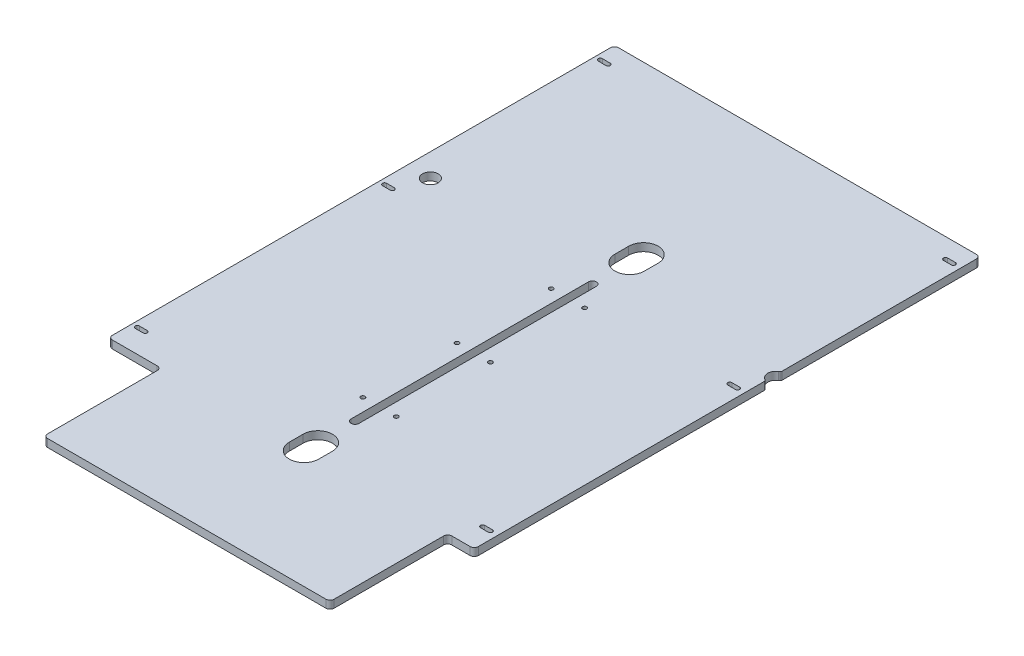
SolidWorks part; units mm, degrees
material "PE High Density"
ref_plane "Front" through (0, 0, 0) normal (0, 0, 1) x (1, 0, 0)
ref_plane "Top" through (0, 0, 0) normal (0, 1, 0) x (1, 0, 0)
ref_plane "Right" through (0, 0, 0) normal (1, 0, 0) x (0, 0, -1)
sketch "Sketch1" plane through (0, 0, 0) normal (0, 1, 0) x (1, 0, 0)
  line L0 (0, 0) -> (96.0438, 0)
  line L1 (96.0438, 0) -> (96.0438, -190.5)
  line L2 (96.0438, -190.5) -> (559.5938, -190.5)
  line L3 (559.5938, -190.5) -> (559.5938, 0)
  line L4 (559.5938, 0) -> (606.425, 0)
  line L5 (606.425, 0) -> (606.425, 819.15)
  line L6 (606.425, 819.15) -> (0, 819.15)
  line L7 (0, 819.15) -> (0, 0)
  line L8 (25.4, 0) -> (25.4, 819.15) construction
  line L9 (19.05, 38.1) -> (31.75, 38.1) construction
  line L10 (19.05, 41.4782) -> (31.75, 41.4782)
  line L11 (19.05, 34.7218) -> (31.75, 34.7218)
  line L12 (19.05, 438.15) -> (31.75, 438.15) construction
  line L13 (19.05, 441.5282) -> (31.75, 441.5282)
  line L14 (19.05, 434.7718) -> (31.75, 434.7718)
  line L15 (31.75, 787.4) -> (19.05, 787.4) construction
  line L16 (31.75, 784.0218) -> (19.05, 784.0218)
  line L17 (31.75, 790.7782) -> (19.05, 790.7782)
  line L18 (303.2125, 819.15) -> (303.2125, -190.5) construction
  line L19 (584.2, 787.4) -> (584.2, 438.15) construction
  line L20 (577.85, 787.4) -> (590.55, 787.4) construction
  line L21 (577.85, 784.0218) -> (590.55, 784.0218)
  line L22 (577.85, 790.7782) -> (590.55, 790.7782)
  line L23 (590.55, 438.15) -> (577.85, 438.15) construction
  line L24 (590.55, 441.5282) -> (577.85, 441.5282)
  line L25 (590.55, 434.7718) -> (577.85, 434.7718)
  line L26 (590.55, 38.1) -> (577.85, 38.1) construction
  line L27 (590.55, 41.4782) -> (577.85, 41.4782)
  line L28 (590.55, 34.7218) -> (577.85, 34.7218)
  line L29 (327.8187, -190.5) -> (327.8187, 819.15) construction
  line L30 (584.2, 438.15) -> (584.2, 38.1) construction
  arc A1 (19.05, 41.4782) -> (19.05, 34.7218) centre (19.05, 38.1) ccw
  arc A2 (31.75, 34.7218) -> (31.75, 41.4782) centre (31.75, 38.1) ccw
  arc A3 (19.05, 441.5282) -> (19.05, 434.7718) centre (19.05, 438.15) ccw
  arc A4 (31.75, 434.7718) -> (31.75, 441.5282) centre (31.75, 438.15) ccw
  arc A5 (31.75, 784.0218) -> (31.75, 790.7782) centre (31.75, 787.4) ccw
  arc A6 (19.05, 790.7782) -> (19.05, 784.0218) centre (19.05, 787.4) ccw
  arc A7 (577.85, 784.0218) -> (577.85, 790.7782) centre (577.85, 787.4) cw
  arc A8 (590.55, 790.7782) -> (590.55, 784.0218) centre (590.55, 787.4) cw
  arc A9 (590.55, 441.5282) -> (590.55, 434.7718) centre (590.55, 438.15) cw
  arc A10 (577.85, 434.7718) -> (577.85, 441.5282) centre (577.85, 438.15) cw
  arc A11 (590.55, 41.4782) -> (590.55, 34.7218) centre (590.55, 38.1) cw
  arc A12 (577.85, 34.7218) -> (577.85, 41.4782) centre (577.85, 38.1) cw
  point P13 (25.4, 38.1)
  point P20 (25.4, 438.15)
  point P27 (25.4, 787.4)
  point P38 (584.2, 787.4)
  point P45 (584.2, 438.15)
  point P52 (584.2, 38.1)
  dimension "D1" = 96.0438
  dimension "D2" = 46.8312
  dimension "D3" = 819.15
  dimension "D4" = 25.4
  dimension "D5" = 6.7564
  dimension "D6" = 38.1
  dimension "D7" = 12.7
  dimension "D8" = 400.05
  dimension "D9" = 349.25
  dimension "D10" = 190.5
  dimension "D11" = 463.55
  dimension "D12" = 22.225
extrude "Boss-Extrude1" add sketch "Sketch1" along normal blind 12.7
fillet "Fillet1" radius 6.604 2 edges at (96.0438, 6.35, 0) (559.5938, 6.35, 0)
fillet "Fillet2" radius 6.604 6 edges at (0, 6.35, -819.15) (606.425, 6.35, -819.15) (606.425, 6.35, 0) (559.5938, 6.35, 190.5) (0, 6.35, 0) (96.0438, 6.35, 190.5)
sketch "Sketch2" plane through (0, 12.7, 0) normal (0, 1, 0) x (1, 0, 0)
  line L1 (606.425, 6.604) -> (606.425, 812.546) construction
  line L3 (577.85, 438.15) -> (590.55, 438.15) construction
  line L4 (606.425, 505.867) -> (606.425, 461.873)
  line L5 (606.425, 483.87) -> (47.625, 483.87) construction
  line L6 (0, 812.546) -> (0, 6.604) construction
  arc A3 (600.075, 494.8685) -> (600.075, 472.8715) centre (606.425, 483.87) ccw
  arc A4 (600.075, 494.8685) -> (606.425, 505.867) centre (593.725, 505.867) ccw
  arc A5 (606.425, 461.873) -> (600.075, 472.8715) centre (593.725, 461.873) ccw
  circle A6 centre (47.625, 483.87) radius 12.7
  dimension "D1" = 25.4
  dimension "D2" = 45.72
  dimension "D3" = 47.625
extrude "Cut-Extrude1" cut sketch "Sketch2" against normal through all
sketch "Sketch4" plane through (0, 0, 0) normal (0, -1, 0) x (1, 0, 0)
  line L0 (0, -812.546) -> (0, -6.604) construction
  line L3 (327.025, -527.05) -> (327.025, -549.275) construction
  line L4 (350.8375, -527.05) -> (350.8375, -549.275)
  line L5 (303.2125, -527.05) -> (303.2125, -549.275)
  line L7 (599.821, -819.15) -> (6.604, -819.15) construction
  line L8 (327.025, 0) -> (327.025, -22.225) construction
  line L9 (350.8375, 0) -> (350.8375, -22.225)
  line L10 (303.2125, 0) -> (303.2125, -22.225)
  circle A0 centre (327.025, -538.1625) radius 28.575 construction
  arc A2 (350.8375, -527.05) -> (303.2125, -527.05) centre (327.025, -527.05) ccw
  arc A3 (303.2125, -549.275) -> (350.8375, -549.275) centre (327.025, -549.275) ccw
  arc A4 (350.8375, 0) -> (303.2125, 0) centre (327.025, 0) ccw
  arc A5 (303.2125, -22.225) -> (350.8375, -22.225) centre (327.025, -22.225) ccw
  point P8 (327.025, -11.1125)
  point P12 (327.025, -538.1625)
  dimension "D2" = 57.15
  dimension "D1" = 327.025
  dimension "D3" = 527.05
  dimension "D4" = 47.625
  dimension "D5" = 22.225
  dimension "D6" = 280.9875
extrude "Cut-Extrude3" cut sketch "Sketch4" against normal through all
sketch "Sketch5" plane through (0, 0, 0) normal (0, -1, 0) x (1, 0, 0)
  line L0 (327.025, -22.225) -> (327.025, -527.05) construction
  line L1 (327.025, -466.725) -> (327.025, -82.55) construction
  line L2 (320.675, -466.725) -> (320.675, -82.55)
  line L3 (333.375, -466.725) -> (333.375, -82.55)
  arc A0 (320.675, -466.725) -> (333.375, -466.725) centre (327.025, -466.725) ccw
  arc A1 (333.375, -82.55) -> (320.675, -82.55) centre (327.025, -82.55) ccw
  point P6 (327.025, -274.6375)
  dimension "D1" = 384.175
  dimension "D2" = 12.7
extrude "Cut-Extrude4" cut sketch "Sketch5" against normal through all
sketch "Sketch6" plane through (0, 0, 0) normal (0, -1, 0) x (1, 0, 0)
  line L0 (327.025, -82.55) -> (327.025, -466.725) construction
  line L1 (327.025, -274.6375) -> (354.0125, -274.6375) construction
  line L2 (354.0125, -122.2375) -> (354.0125, -427.0375) construction
  line L3 (300.0375, -122.2375) -> (300.0375, -427.0375) construction
  circle A0 centre (354.0125, -274.6375) radius 3.3782
  circle A1 centre (354.0125, -427.0375) radius 3.3782
  circle A2 centre (354.0125, -122.2375) radius 3.3782
  circle A3 centre (300.0375, -427.0375) radius 3.3782
  circle A4 centre (300.0375, -274.6375) radius 3.3782
  circle A5 centre (300.0375, -122.2375) radius 3.3782
  dimension "D2" = 6.7564
  dimension "D1" = 26.9875
  dimension "D3" = 152.4
extrude "Cut-Extrude5" cut sketch "Sketch6" against normal through all
sketch "Sketch7" plane through (0, 0, 0) normal (0, -1, 0) x (1, 0, 0)
  line L0 (599.821, -819.15) -> (6.604, -819.15) construction
  line L1 (6.604, 0) -> (89.4398, 0) construction
  line L2 (0, -812.546) -> (0, -6.604) construction
  line L3 (7.366, -819.15) -> (6.604, -819.15)
  line L4 (6.604, 0) -> (7.366, 0)
  line L5 (0, -812.546) -> (0, -6.604)
  line L6 (0.762, -6.604) -> (0.762, -812.546)
  line L7 (566.1978, 0) -> (599.821, 0) construction
  line L8 (606.425, -505.867) -> (606.425, -812.546) construction
  line L9 (606.425, -6.604) -> (606.425, -461.873) construction
  line L10 (566.1978, 0) -> (599.821, 0)
  line L11 (599.821, -819.15) -> (6.604, -819.15)
  line L12 (606.425, -505.867) -> (606.425, -812.546)
  line L13 (606.425, -6.604) -> (606.425, -461.873)
  line L14 (605.663, -504.5472) -> (605.663, -812.546)
  line L15 (605.663, -6.604) -> (605.663, -462.3309)
  arc A0 (0, -812.546) -> (6.604, -819.15) centre (6.604, -812.546) ccw construction
  arc A1 (6.604, 0) -> (0, -6.604) centre (6.604, -6.604) ccw construction
  arc A2 (0, -812.546) -> (6.604, -819.15) centre (6.604, -812.546) ccw
  arc A3 (6.604, 0) -> (0, -6.604) centre (6.604, -6.604) ccw
  arc A4 (7.366, 0) -> (0.762, -6.604) centre (7.366, -6.604) ccw
  arc A5 (0.762, -812.546) -> (7.366, -819.15) centre (7.366, -812.546) ccw
  arc A6 (599.821, -819.15) -> (606.425, -812.546) centre (599.821, -812.546) ccw construction
  arc A7 (606.425, -505.867) -> (600.075, -494.8685) centre (593.725, -505.867) ccw construction
  arc A8 (600.075, -472.8715) -> (600.075, -494.8685) centre (606.425, -483.87) ccw construction
  arc A9 (600.075, -472.8715) -> (606.425, -461.873) centre (593.725, -461.873) ccw construction
  arc A10 (606.425, -6.604) -> (599.821, 0) centre (599.821, -6.604) ccw construction
  arc A11 (599.821, -819.15) -> (606.425, -812.546) centre (599.821, -812.546) ccw
  arc A12 (606.425, -505.867) -> (600.075, -494.8685) centre (593.725, -505.867) ccw
  arc A13 (600.075, -472.8715) -> (600.075, -494.8685) centre (606.425, -483.87) ccw
  arc A14 (600.075, -472.8715) -> (606.425, -461.873) centre (593.725, -461.873) ccw
  arc A15 (606.425, -6.604) -> (599.821, 0) centre (599.821, -6.604) ccw
  arc A16 (605.663, -6.604) -> (599.059, 0) centre (599.059, -6.604) ccw
  arc A17 (599.059, -819.15) -> (605.663, -812.546) centre (599.059, -812.546) ccw
  arc A18 (605.663, -504.5472) -> (600.075, -494.8685) centre (594.487, -504.5472) ccw
  arc A19 (599.694, -473.1004) -> (605.663, -462.3309) centre (592.963, -462.3309) ccw
  dimension "D1" = 0.762
  dimension "D2" = 0.762
extrude "Cut-Extrude6" cut sketch "Sketch7" against normal through all contours A18 L14 A17 L11 A11 L12 A12 | A5 L6 A4 L4 A3 L5 A2 L3 | A19 A13 A14 L13 A15 L10 A16 L15
sketch "Sketch8" plane through (0, 0, 0) normal (0, -1, 0) x (1, 0, 0)
  line L0 (0.762, -6.604) -> (0.762, -812.546) construction
  line L1 (0.762, -6.604) -> (0.762, -812.546)
  line L2 (605.663, -6.604) -> (605.663, -462.3309) construction
  line L3 (605.663, -6.604) -> (605.663, -812.546)
  line L4 (10.287, -6.604) -> (10.287, -812.546)
  line L5 (16.891, 0) -> (7.366, 0)
  line L6 (16.891, -819.15) -> (7.366, -819.15)
  line L7 (602.488, -6.604) -> (602.488, -812.546)
  line L8 (599.059, -819.15) -> (595.884, -819.15)
  line L9 (599.059, 0) -> (595.884, 0)
  arc A0 (0.762, -812.546) -> (7.366, -819.15) centre (7.366, -812.546) ccw construction
  arc A1 (7.366, 0) -> (0.762, -6.604) centre (7.366, -6.604) ccw construction
  arc A2 (0.762, -812.546) -> (7.366, -819.15) centre (7.366, -812.546) ccw
  arc A3 (7.366, 0) -> (0.762, -6.604) centre (7.366, -6.604) ccw
  arc A4 (599.059, -819.15) -> (605.663, -812.546) centre (599.059, -812.546) ccw construction
  arc A5 (605.663, -6.604) -> (599.059, 0) centre (599.059, -6.604) ccw construction
  arc A6 (599.059, -819.15) -> (605.663, -812.546) centre (599.059, -812.546) ccw
  arc A7 (605.663, -6.604) -> (599.059, 0) centre (599.059, -6.604) ccw
  arc A8 (16.891, 0) -> (10.287, -6.604) centre (16.891, -6.604) ccw
  arc A9 (10.287, -812.546) -> (16.891, -819.15) centre (16.891, -812.546) ccw
  arc A10 (602.488, -6.604) -> (595.884, 0) centre (595.884, -6.604) ccw
  arc A11 (595.884, -819.15) -> (602.488, -812.546) centre (595.884, -812.546) ccw
  dimension "D2" = 9.525
  dimension "D4" = 3.175
  dimension "D1" = 2
  dimension "D3" = 2
extrude "Cut-Extrude7" cut sketch "Sketch8" against normal through all contours L1 A2 L6 A9 L4 A8 L5 A3 | L7 A11 L8 A6 L3 A7 L9 A10
fillet "Fillet3" radius 2.54 2 edges at (602.488, 6.35, -470.7311) (602.488, 6.35, -496.7442)
